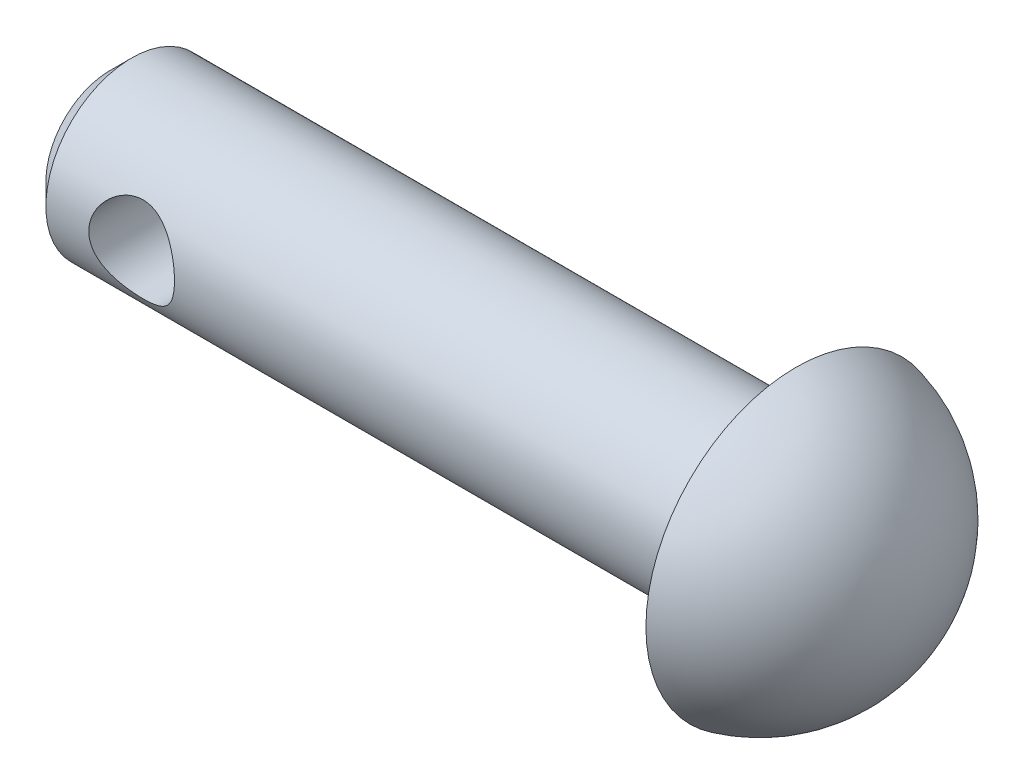
SolidWorks part; units mm, degrees
ref_plane "Front Plane" through (0, 0, 0) normal (0, 0, 1) x (1, 0, 0)
ref_plane "Top Plane" through (0, 0, 0) normal (0, 1, 0) x (1, 0, 0)
ref_plane "Right Plane" through (0, 0, 0) normal (1, 0, 0) x (0, 0, -1)
sketch "Sketch1" plane through (0, 0, 0) normal (1, 0, 0) x (0, 0, -1)
  circle A0 centre (0, 0) radius 2
  dimension "D1" = 4
extrude "Boss-Extrude1" add sketch "Sketch1" against normal blind 16
sketch "Sketch2" plane through (0, 0, 0) normal (0, 0, 1) x (1, 0, 0)
  line L0 (-16, 2) -> (-16, -2) construction
  circle A0 centre (-13.5, 0) radius 1
  point P4 (0, 0)
  dimension "D1" = 2
  dimension "D2" = 2.5
extrude "Cut-Extrude1" cut sketch "Sketch2" against normal mid plane 16
sketch "Sketch3" plane through (0, 0, 0) normal (0, 1, 0) x (1, 0, 0)
  line L0 (-4.4426, 0) -> (4.4362, 0) construction
  line L1 (0, 3.5) -> (0, 0)
  line L2 (0, 0) -> (2.7574, 0)
  arc A0 (0, 3.5) -> (2.7574, 0) centre (-0.8426, 0) cw
  point P7 (0, 0)
  point P8 (0, 0)
  dimension "D1" = 3.5
  dimension "D2" = 3.6
revolve "Revolve1" add sketch "Sketch3" angle 360 about L0
chamfer "Chamfer1" distance 0.5 angle 45 1 edges at (-16, 0, -2)
